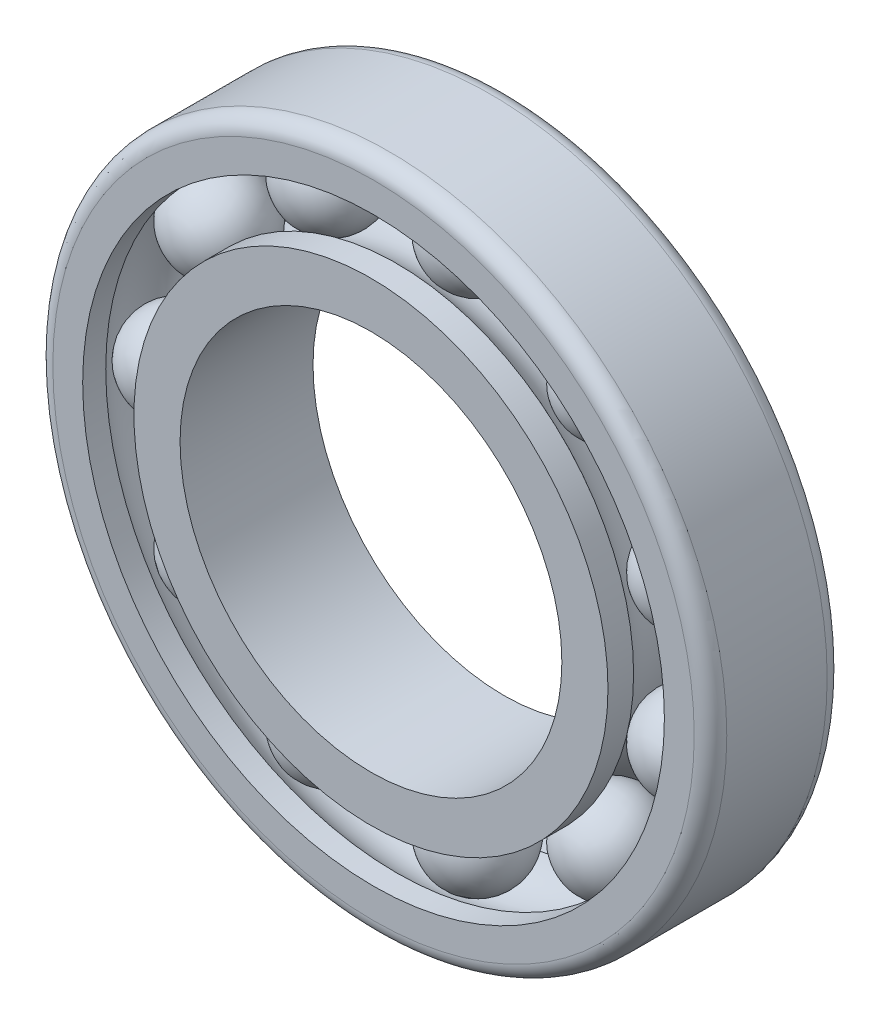
SolidWorks part; units mm, degrees
material "Alloy Steel"
ref_plane "Front Plane" through (0, 0, 0) normal (0, 0, 1) x (1, 0, 0)
ref_plane "Top Plane" through (0, 0, 0) normal (0, 1, 0) x (1, 0, 0)
ref_plane "Right Plane" through (0, 0, 0) normal (1, 0, 0) x (0, 0, -1)
sketch "Croquis1" plane through (0, 0, 0) normal (0, 1, 0) x (1, 0, 0)
  line L0 (-62.1, -12.25) -> (-35.18, 11.777) construction
  line L1 (-62.1, 12.25) -> (-53.6, 12.25)
  line L2 (-62.1, 12.25) -> (-62.1, -12.25)
  line L3 (-62.1, -12.25) -> (-53.6, -12.25)
  line L4 (-53.6, 12.25) -> (-53.6, 7.5274)
  line L5 (-62.1, 12.25) -> (-57.85, 0) construction
  line L6 (-62.1, -12.25) -> (-57.85, 0) construction
  line L7 (-43.68, 11.777) -> (-35.18, 11.777)
  line L8 (-43.68, 11.777) -> (-43.68, 11.5415)
  line L9 (-43.68, -12.723) -> (-35.18, -12.723)
  line L10 (-35.18, 11.777) -> (-35.18, -12.723)
  line L11 (-41.6032, 6.044) -> (-41.4066, 5.4694) construction
  line L13 (0, 0) -> (0, 0.7689) construction
  line L14 (-43.68, 11.5415) -> (-43.68, 7.5274)
  line L15 (-53.6, -8.0004) -> (-53.6, -12.25)
  line L16 (-43.68, -8.0004) -> (-43.68, -12.723)
  line L17 (-56.0175, 5.2818) -> (-53.6, 12.25) construction
  line L18 (-55.7246, -6.1263) -> (-55.6097, -6.4572) construction
  line L19 (-39.387, -0.4313) -> (-35.18, -12.723) construction
  line L20 (-39.387, -0.4313) -> (-35.18, 11.777) construction
  arc A0 (-53.6, 7.5274) -> (-53.6, -8.0004) centre (-48.64, -0.2365) ccw
  arc A1 (-43.68, -8.0004) -> (-43.68, 7.5274) centre (-48.64, -0.2365) ccw
  point P0 (-57.85, 0)
  point P5 (-39.5346, 0)
  dimension "D1" = 24.5
  dimension "D2" = 8.5
  dimension "D3" = 62.1
  dimension "D4" = 35.18
sketch "Croquis2" plane through (0, 0, 0) normal (0, 1, 0) x (1, 0, 0)
  line L1 (-48.375, -8.5276) -> (-48.375, 8.5276)
  arc A1 (-48.375, 8.5276) -> (-48.375, -8.5276) centre (-48.375, 0) cw
revolve "Revolución1" add sketch "Croquis2" angle 360 about L1
revolve "Revolución2" add sketch "Croquis1" angle 360 about L13
pattern_circular "MatrizC1" count 11 over 360 about axis through (0, 0, 0) along (0, 0, 1) of bodies 125
fillet "Redondeo1" radius 3 2 edges at (62.1, 0, -12.25) (62.1, 0, 12.25)
